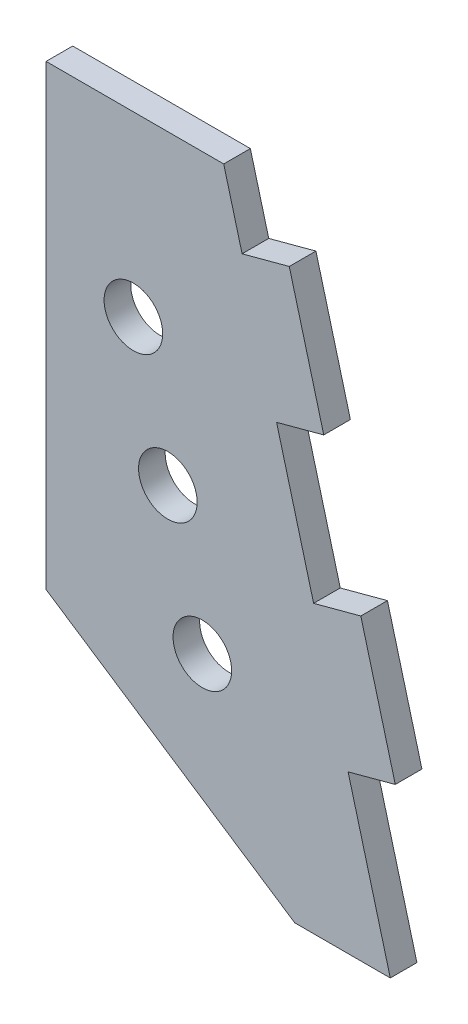
SolidWorks part; units mm, degrees
material "AISI 4340 Aço, normalizado"
ref_plane "Plano frontal" through (0, 0, 0) normal (0, 0, 1) x (1, 0, 0)
ref_plane "Plano superior" through (0, 0, 0) normal (0, 1, 0) x (1, 0, 0)
ref_plane "Plano direito" through (0, 0, 0) normal (1, 0, 0) x (0, 0, -1)
sketch "Esboço1" plane through (0, 0, 0) normal (0, 0, 1) x (1, 0, 0)
  line L0 (0, 0) -> (0, 60)
  line L1 (0, 60) -> (20, 60)
  line L2 (20, 60) -> (36.077, 0)
  line L3 (36.077, 0) -> (0, 0)
  dimension "D1" = 75
  dimension "D2" = 60
  dimension "D3" = 20
extrude "Ressalto-extrusão1" add sketch "Esboço1" along normal blind 3
hole_wizard "Furo com folga de M61" positions "Esboço2" profile "Esboço3" hole size "M6" standard "ISO" end condition through all
sketch "Esboço2" plane through (0, 0, 3) normal (0, 0, 1) x (1, 0, 0)
  line L0 (9.8298, 40) -> (17.5944, 11.0222) construction
  line L7 (36.077, 0) -> (20, 60) construction
  line L9 (20, 60) -> (0, 60) construction
  point P0 (9.8298, 40)
  point P2 (13.7121, 25.5111)
  point P4 (17.5944, 11.0222)
  dimension "D1" = 15
  dimension "D2" = 20
  dimension "D3" = 15
  dimension "D4" = 15
sketch "Esboço3" plane through (9.8298, 40, 3) normal (1, 0, 0) x (0, -1, 0)
  line L0 (0, 0) -> (0, 3)
  line L1 (0, 3) -> (3.3, 3)
  line L2 (3.3, 3) -> (3.3, 0)
  line L5 (3.3, 0) -> (0, 0)
  line L11 (0, -6.35) -> (0, 107.95) construction
  dimension "Thru Hole Dia." = 6.6
  dimension "Thru Hole Depth" = 3
sketch "Esboço4" plane through (0, 0, 3) normal (0, 0, 1) x (1, 0, 0)
  line L0 (22.0706, 52.2726) -> (27.3831, 53.6961)
  line L1 (36.077, 0) -> (20, 60) construction
  line L2 (27.3831, 53.6961) -> (31.2654, 39.2072)
  line L3 (31.2654, 39.2072) -> (25.9528, 37.7837)
  line L4 (30.1241, 22.2163) -> (35.4367, 23.6398)
  line L5 (35.4367, 23.6398) -> (39.319, 9.1509)
  line L6 (39.319, 9.1509) -> (34.0064, 7.7274)
  line L7 (34.0064, 7.7274) -> (30.1241, 22.2163)
  line L8 (22.0706, 52.2726) -> (25.9528, 37.7837)
  dimension "D1" = 5.5
  dimension "D2" = 5.5
  dimension "D3" = 15
  dimension "D4" = 15
  dimension "D5" = 8
  dimension "D6" = 8
extrude "Ressalto-extrusão2" add sketch "Esboço4" against normal blind 3
sketch "Esboço5" plane through (0, 0, 3) normal (0, 0, 1) x (1, 0, 0)
  line L0 (0, 0) -> (0, -10)
  line L1 (0, -10) -> (38.7564, -10)
  line L2 (38.7564, -10) -> (36.077, 0)
  line L3 (36.077, 0) -> (0, 0)
  line L4 (36.077, 0) -> (34.0064, 7.7274) construction
  dimension "D1" = 10
extrude "Ressalto-extrusão3" add sketch "Esboço5" against normal blind 3
sketch "Esboço6" plane through (0, 0, 3) normal (0, 0, 1) x (1, 0, 0)
  line L0 (0, -10) -> (0, 8.5)
  line L1 (0, 60) -> (0, -10) construction
  line L2 (0, 8.5) -> (28, -10)
  line L3 (0, -10) -> (38.7564, -10) construction
  line L4 (0, -10) -> (28, -10)
  line L5 (0, -10) -> (0, 8.5)
  line M7 (0, 60) -> (0, -10)
  line M8 (0, -10) -> (38.7564, -10)
  dimension "D1" = 18.5
  dimension "D2" = 28
extrude "Corte-extrusão1" cut sketch "Esboço6" against normal through all contours L2 M7 M8
